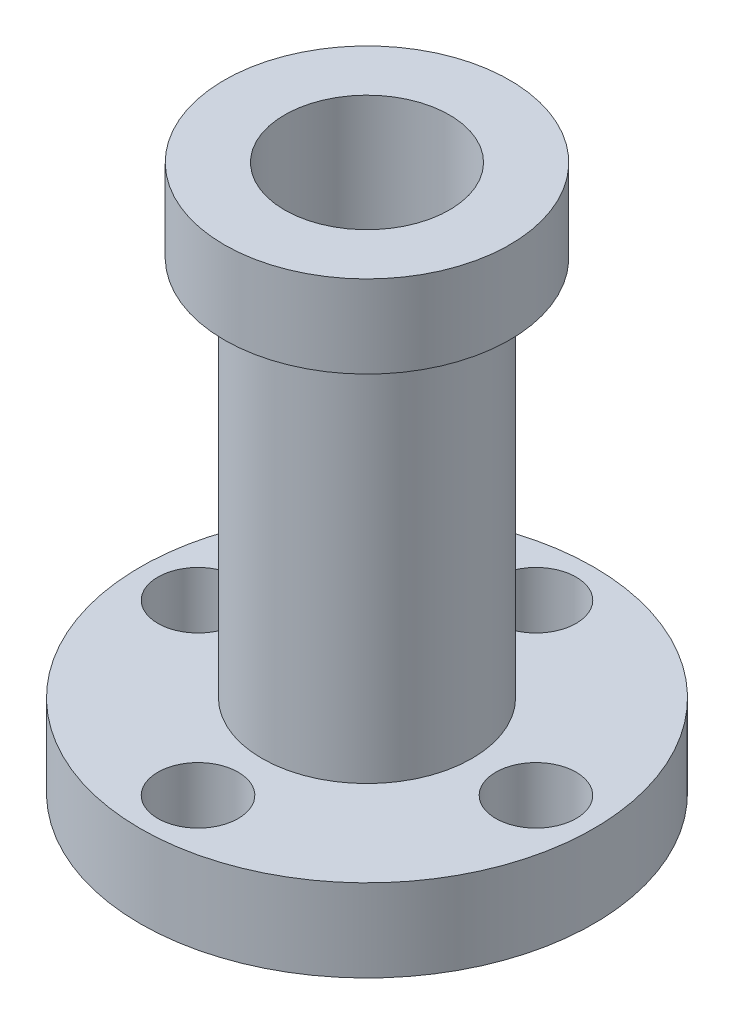
SolidWorks part; units mm, degrees
material "Brass"
ref_plane "Front" through (0, 0, 0) normal (0, 0, 1) x (1, 0, 0)
ref_plane "Top" through (0, 0, 0) normal (0, 1, 0) x (1, 0, 0)
ref_plane "Right" through (0, 0, 0) normal (1, 0, 0) x (0, 0, -1)
sketch "Sketch1" plane through (0, 0, 0) normal (0, 1, 0) x (1, 0, 0)
  line L0 (0, 0) -> (-14.5379, 0) construction
  line L1 (0, 0) -> (0, 15.4966) construction
  circle A0 centre (0, 0) radius 11
  circle A1 centre (-8.2, 0) radius 1.95
  circle A2 centre (8.2, 0) radius 1.95
  circle A3 centre (0, 8.2) radius 1.95
  circle A4 centre (0, 0) radius 8.2 construction
  circle A5 centre (0, -8.2) radius 1.95
  dimension "D1" = 22
  dimension "D2" = 12.5
  dimension "D3" = 3.9
extrude "Boss-Extrude1" add sketch "Sketch1" along normal blind 4
sketch "Sketch2" plane through (0, 4, 0) normal (0, 1, 0) x (1, 0, 0)
  circle A0 centre (0, 0) radius 5.1
  dimension "D1" = 10.2
extrude "Boss-Extrude2" add sketch "Sketch2" along normal blind 18.5
sketch "Sketch3" plane through (0, 22.5, 0) normal (0, 1, 0) x (1, 0, 0)
  circle A0 centre (0, 0) radius 6.925
  circle A1 centre (0, 0) radius 5.1 construction
  dimension "D1" = 13.85
extrude "Boss-Extrude3" add sketch "Sketch3" along normal blind 4
sketch "Sketch4" plane through (0, 26.5, 0) normal (0, 1, 0) x (1, 0, 0)
  circle A0 centre (0, 0) radius 4
  dimension "D1" = 8
extrude "Cut-Extrude1" cut sketch "Sketch4" against normal through all
